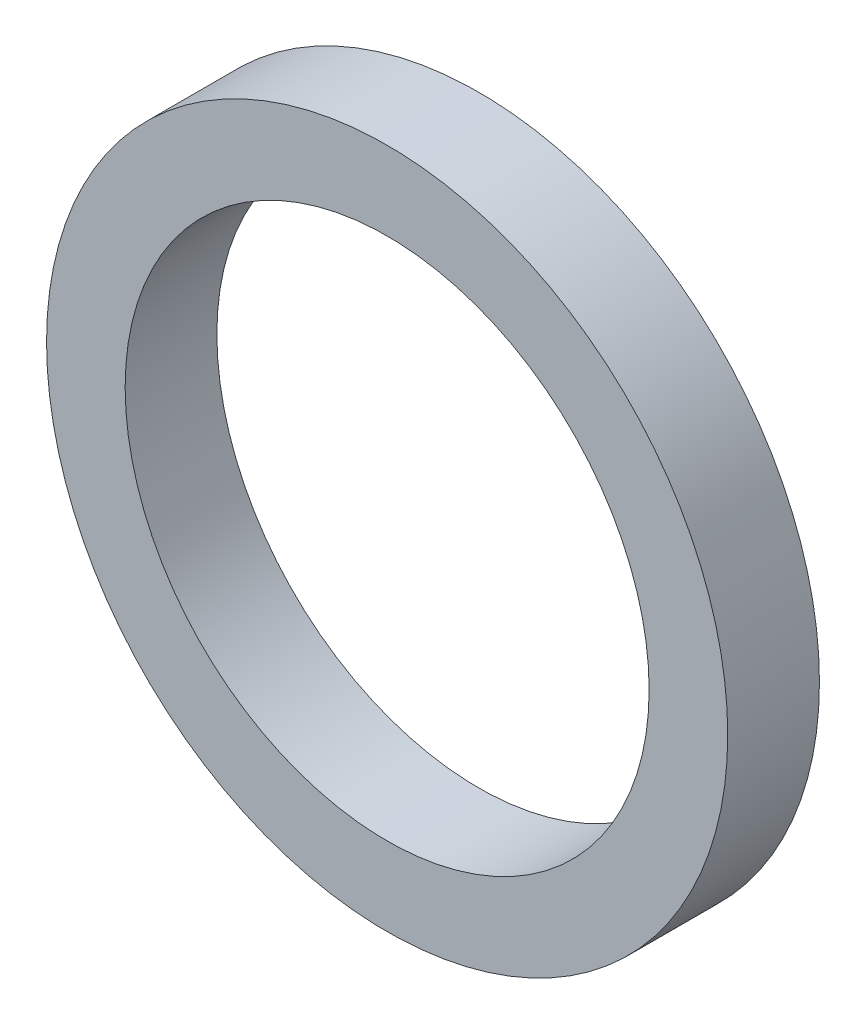
SolidWorks part; units mm, degrees
ref_plane "前视基准面" through (0, 0, 0) normal (0, 0, 1) x (1, 0, 0)
ref_plane "上视基准面" through (0, 0, 0) normal (0, 1, 0) x (1, 0, 0)
ref_plane "右视基准面" through (0, 0, 0) normal (1, 0, 0) x (0, 0, -1)
sketch "草图1" plane through (0, 0, 0) normal (0, 0, 1) x (1, 0, 0)
  circle A0 centre (0, 0) radius 20
  circle A1 centre (0, 0) radius 26
  dimension "D1" = 40
  dimension "D2" = 52
extrude "凸台-拉伸1" add sketch "草图1" along normal blind 7
